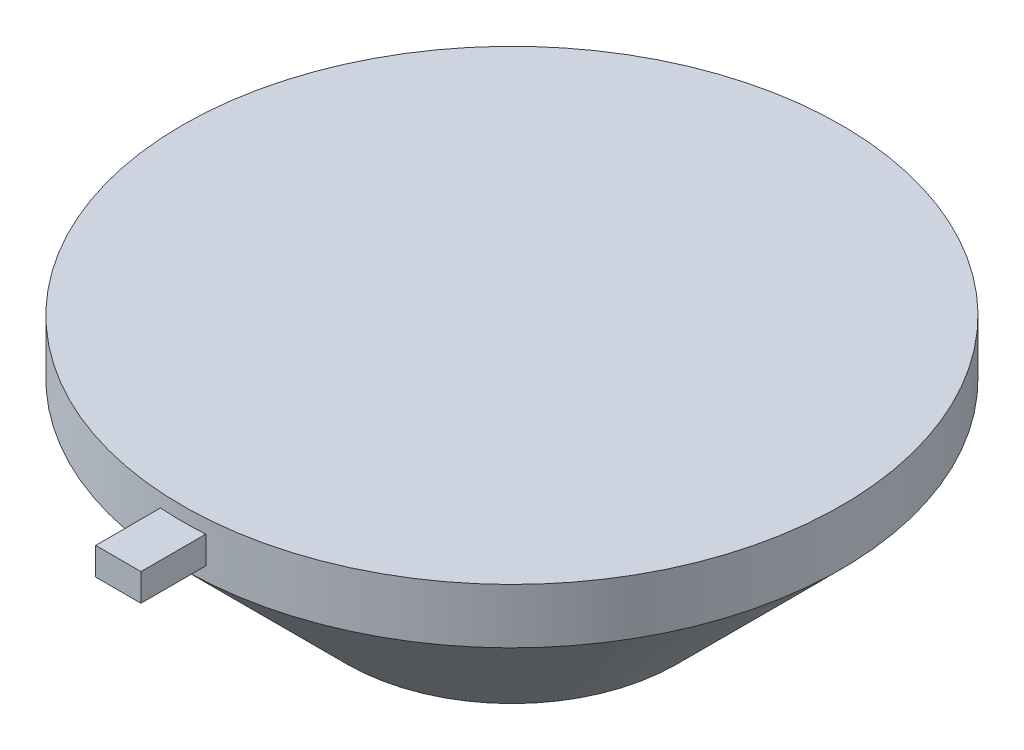
SolidWorks part; units mm, degrees
ref_plane "Front Plane" through (0, 0, 0) normal (0, 0, 1) x (1, 0, 0)
ref_plane "Top Plane" through (0, 0, 0) normal (0, 1, 0) x (1, 0, 0)
ref_plane "Right Plane" through (0, 0, 0) normal (1, 0, 0) x (0, 0, -1)
sketch "Sketch1" plane through (0, 0, 0) normal (0, 0, 1) x (1, 0, 0)
  line L0 (-42.6436, 0) -> (41.8718, 0) construction
  line L3 (0.389, -0.0678) -> (-5.2268, -4)
  line L4 (0.389, -0.0678) -> (-5.6788, 6)
  line L7 (6.3212, 11.0477) -> (6.3212, -9.609) construction
  line L12 (-5.2268, -4) -> (6.3212, -4)
  line L13 (6.3212, -4) -> (6.3212, 6)
  line L14 (6.3212, 6) -> (-5.6788, 6)
  point P3 (-0.3859, 0)
  point P4 (-16.1486, 15.7627)
  point P6 (-17.3053, -11.8471)
  point P7 (-17.0185, -12.2567)
  point P8 (-15.795, 16.1162)
  dimension "D6" = 12
revolve "Revolve1" add sketch "Sketch1" angle 360 about L7
scale "Scale1" [suppressed]
split "Split2" trim tools "Top Plane" bodies to split 101 resulting bodies 117 118
sketch "Sketch11" plane through (0, 6, 0) normal (0, 1, 0) x (1, 0, 0)
  circle A0 centre (6.3212, 0) radius 12 construction
  circle A1 centre (6.3212, 0) radius 12
extrude "Boss-Extrude3" add sketch "Sketch11" along normal blind 2
delete or keep bodies "Body-Delete/Keep 2" type delete bodies bodies 118
sketch "Sketch12" plane through (0, 8, 0) normal (0, 1, 0) x (1, 0, 0)
  line L0 (6.3212, 4.2013) -> (6.3212, -17.3603) construction
  line L2 (5.4966, -11.0556) -> (7.1458, -11.0556)
  line L3 (5.4966, -11.0556) -> (5.4966, -14.3323)
  line L4 (5.4966, -14.3323) -> (7.1458, -14.3323)
  line L5 (7.1458, -11.0556) -> (7.1458, -14.3323)
  arc A0 (-7.093, 0) -> (19.7354, 0) centre (6.3212, 0) ccw construction
  point P11 (6.3212, -11.0556)
extrude "Boss-Extrude4" add sketch "Sketch12" against normal blind 1 from offset 0.5 offset against normal yes
sketch "Sketch13" plane through (0, 8, 0) normal (0, 1, 0) x (1, 0, 0)
  line L0 (-4.4, 0) -> (4.4, 0) construction
  circle A0 centre (6.5467, 0) radius 1
  dimension "D1" = 2
sketch "Sketch14" plane through (0, 0, 0) normal (0, -1, 0) x (-1, 0, 0)
  circle A0 centre (-6.5467, 0) radius 1
  dimension "D1" = 2
extrude "Cut-Extrude2" cut sketch "Sketch14" against normal blind 2
